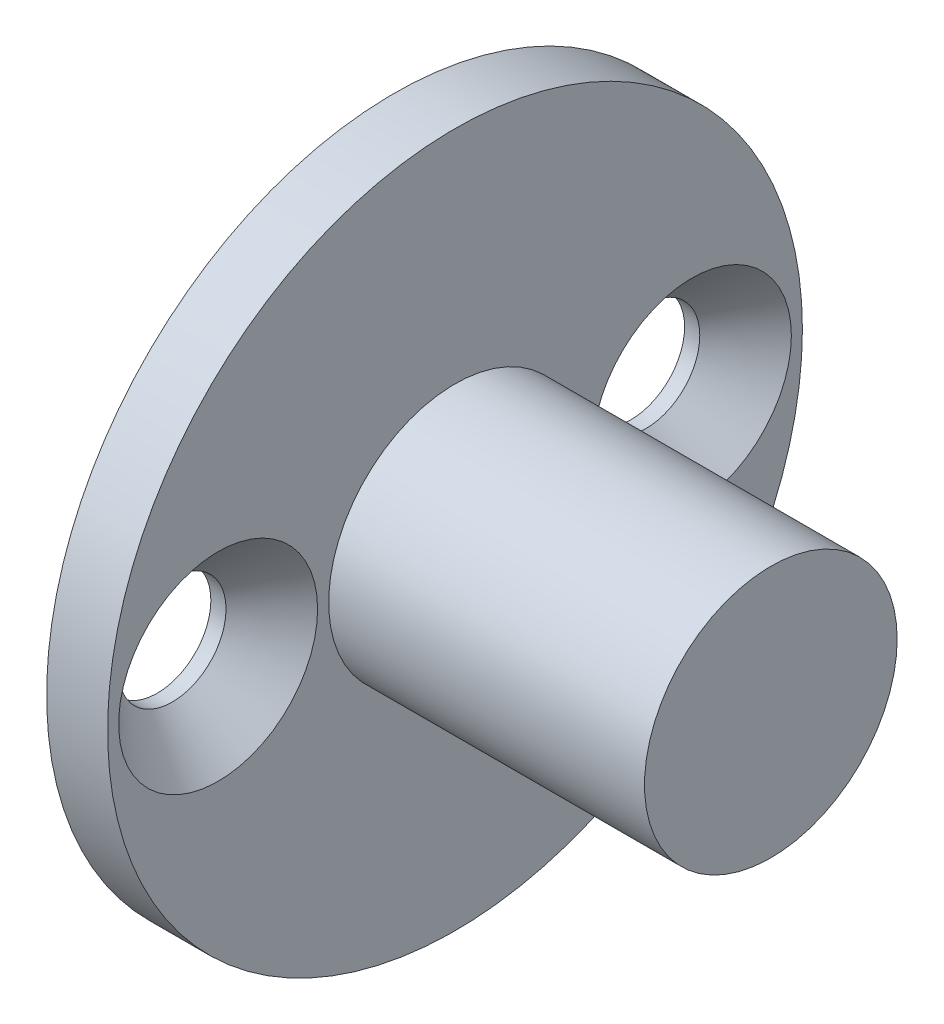
SolidWorks part; units mm, degrees
ref_plane "Front Plane" through (0, 0, 0) normal (0, 0, 1) x (1, 0, 0)
ref_plane "Top Plane" through (0, 0, 0) normal (0, 1, 0) x (1, 0, 0)
ref_plane "Right Plane" through (0, 0, 0) normal (1, 0, 0) x (0, 0, -1)
sketch "Sketch1" plane through (0, 0, 0) normal (1, 0, 0) x (0, 0, -1)
  line L0 (-7.5, 0) -> (7.5, 0) construction
  line L1 (0, -6) -> (0, 6) construction
  circle A0 centre (0, 0) radius 11
  circle A2 centre (0, 6) radius 1.6 construction
  circle A3 centre (7.5, 0) radius 1.6
  circle A4 centre (0, -6) radius 1.6 construction
  circle A5 centre (-7.5, 0) radius 1.6
  point P7 (0, 0)
  point P8 (0, 0)
  point P15 (0, 0)
  dimension "D1" = 22
  dimension "D2" = 12
  dimension "D3" = 3.2
  dimension "D5" = 3.2
  dimension "D6" = 3.2
  dimension "D7" = 3.2
  dimension "D4" = 15
extrude "Boss-Extrude1" add sketch "Sketch1" along normal blind 1.93
sketch "Sketch2" plane through (1.93, 0, 0) normal (1, 0, 0) x (0, 0, -1)
  circle A0 centre (0, 0) radius 4
  dimension "D1" = 8
extrude "Boss-Extrude2" add sketch "Sketch2" along normal blind 10
sketch "Sketch3" plane through (0, 0, 0) normal (1, 0, 0) x (0, 0, -1)
  circle A0 centre (0, 0) radius 2.15
  dimension "D1" = 4.3
extrude "Cut-Extrude1" cut sketch "Sketch3" along normal blind 6
hole_wizard "CSK for M3 Flat Head Machine Screw1" positions "Sketch4" profile "Sketch5" countersink size "M3" standard "ANSI Metric" end condition through all
sketch "Sketch4" plane through (1.93, 0, 0) normal (1, 0, 0) x (0, 0, -1)
  point P0 (-7.5, 0)
  point P3 (7.5, 0)
sketch "Sketch5" plane through (1.93, 0, 7.5) normal (0, 1, 0) x (0, 0, -1)
  line L0 (0, 0) -> (0, 1.93)
  line L1 (0, 1.93) -> (1.7, 1.93)
  line L2 (1.7, 1.93) -> (1.7, 1.45)
  line L3 (1.7, 1.45) -> (3.15, 0)
  line L5 (3.15, 0) -> (0, 0)
  line L6 (-1.7, 1.45) -> (-3.15, 0) construction
  line L11 (0, -6.35) -> (0, 107.95) construction
  dimension "Thru Hole Dia." = 3.4
  dimension "Thru Hole Depth" = 1.93
  dimension "Near C'Sink Dia." = 6.3
  dimension "Near C'Sink Angle" = 90
